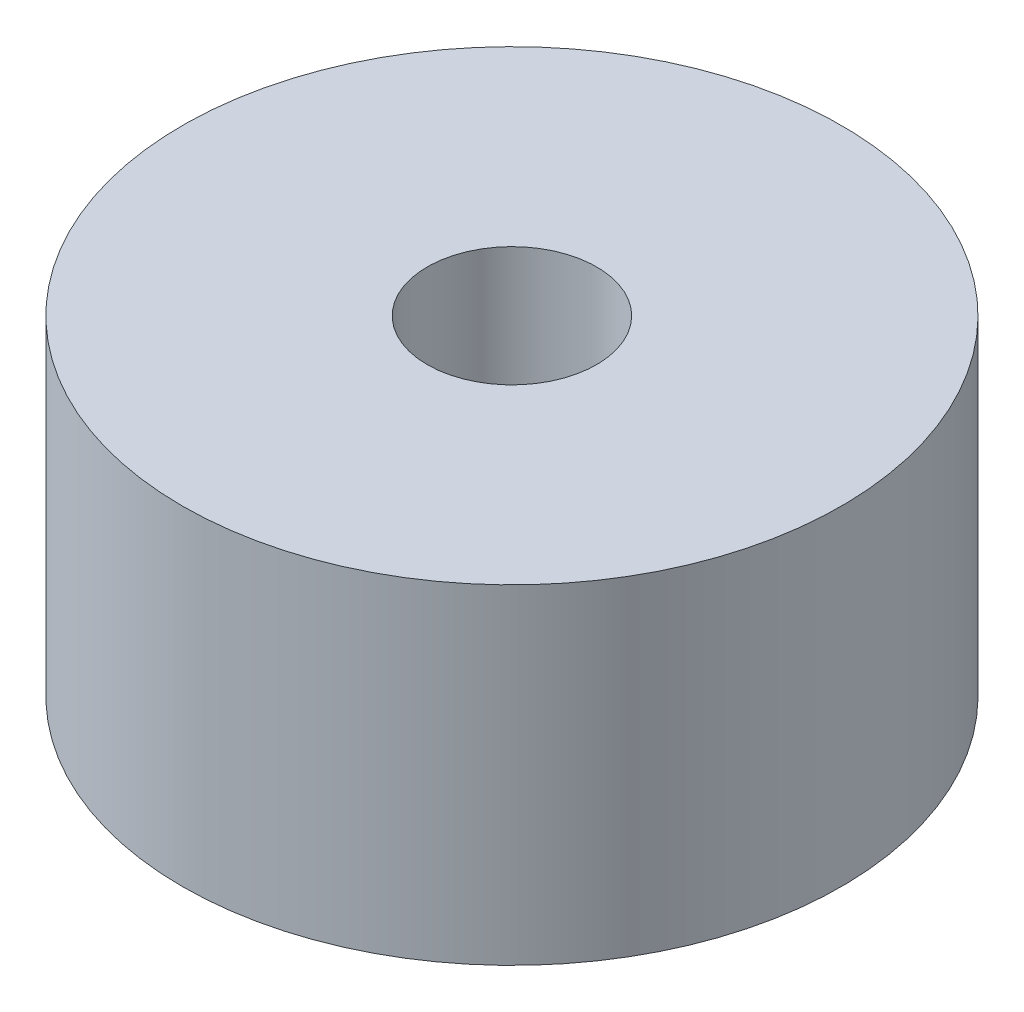
SolidWorks part; units mm, degrees
material "AISI 304"
ref_plane "Front Plane" through (0, 0, 0) normal (0, 0, 1) x (1, 0, 0)
ref_plane "Top Plane" through (0, 0, 0) normal (0, 1, 0) x (1, 0, 0)
ref_plane "Right Plane" through (0, 0, 0) normal (1, 0, 0) x (0, 0, -1)
sketch "Sketch1" plane through (0, 0, 0) normal (0, 1, 0) x (1, 0, 0)
  circle A0 centre (0, 0) radius 12.7
  dimension "D1" = 25.4
extrude "Boss-Extrude1" add sketch "Sketch1" along normal blind 12.7
hole_wizard "1/4 Clearance Hole1" positions "Sketch4" profile "Sketch3" hole size "1/4" standard "ANSI Inch" end condition through all
sketch "Sketch4" plane through (0, 12.7, 0) normal (0, 1, 0) x (1, 0, 0)
  point P0 (0, 0)
sketch "Sketch3" plane through (0, 12.7, 0) normal (1, 0, 0) x (0, 0, 1)
  line L0 (0, 0) -> (0, 12.7)
  line L1 (0, 12.7) -> (3.2639, 12.7)
  line L2 (3.2639, 12.7) -> (3.2639, 0)
  line L5 (3.2639, 0) -> (0, 0)
  line L11 (0, -6.35) -> (0, 107.95) construction
  dimension "Thru Hole Dia." = 6.5278
  dimension "Thru Hole Depth" = 12.7
